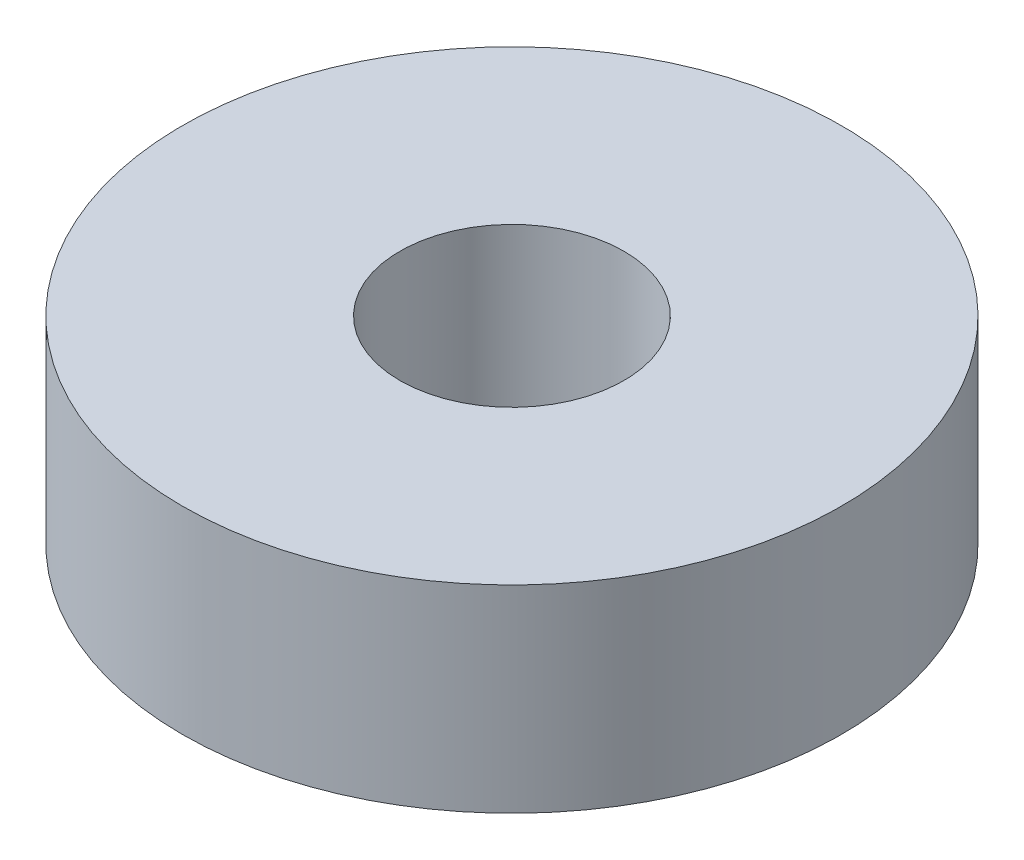
SolidWorks part; units mm, degrees
ref_plane "前视基准面" through (0, 0, 0) normal (0, 0, 1) x (1, 0, 0)
ref_plane "上视基准面" through (0, 0, 0) normal (0, 1, 0) x (1, 0, 0)
ref_plane "右视基准面" through (0, 0, 0) normal (1, 0, 0) x (0, 0, -1)
other "Configuration Table"
sketch "草图1" plane through (0, 0, 0) normal (0, 1, 0) x (1, 0, 0)
  circle A0 centre (0, 0) radius 2.5
  dimension "D1" = 5
extrude "凸台-拉伸1" add sketch "草图1" along normal blind 1.5
sketch "草图2" plane through (0, 1.5, 0) normal (0, 1, 0) x (1, 0, 0)
  circle A0 centre (0, 0) radius 0.85
  dimension "D1" = 1.7
extrude "切除-拉伸1" cut sketch "草图2" against normal through all contours A0
